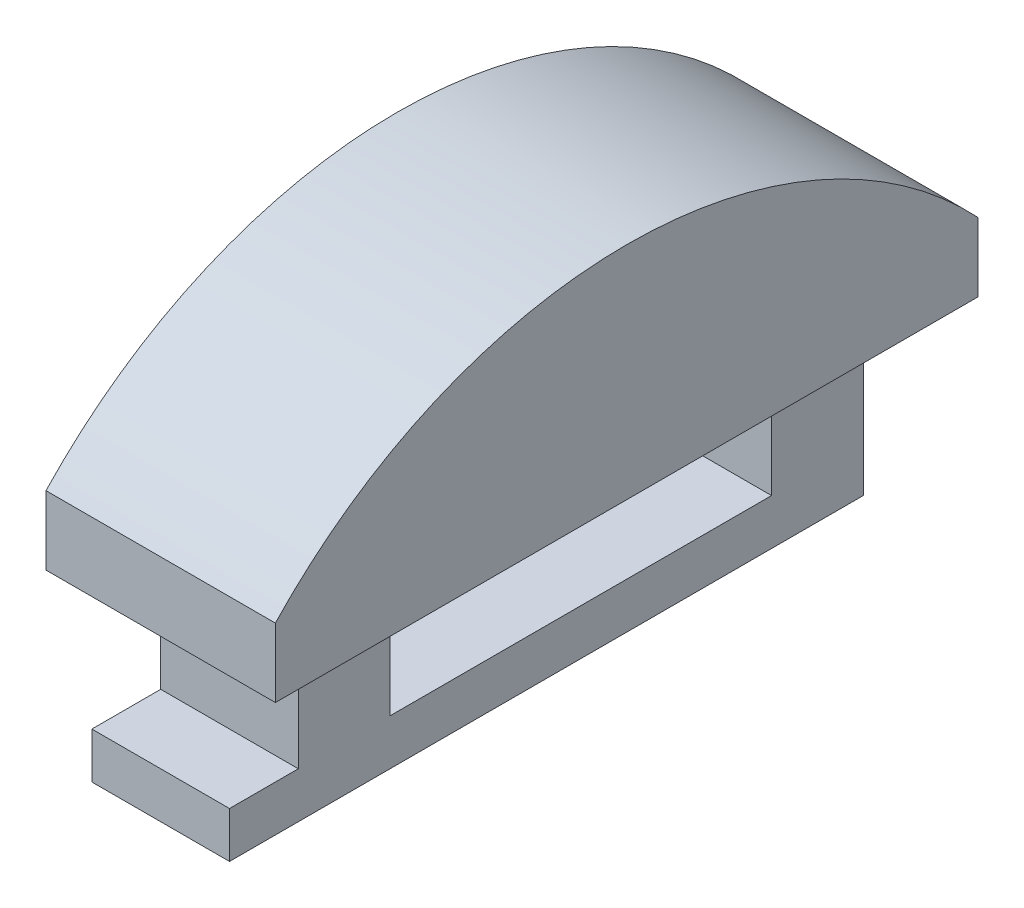
SolidWorks part; units mm, degrees
ref_plane "Спереди" through (0, 0, 0) normal (0, 0, 1) x (1, 0, 0)
ref_plane "Сверху" through (0, 0, 0) normal (0, 1, 0) x (1, 0, 0)
ref_plane "Справа" through (0, 0, 0) normal (1, 0, 0) x (0, 0, -1)
sketch "Эскиз1" plane through (0, 0, 0) normal (0, 1, 0) x (1, 0, 0)
  line L1 (-92.5718, 13.7126) -> (-82.5718, 13.7126)
  line L2 (-92.5718, 13.7126) -> (-92.5718, -16.9174)
  line L3 (-92.5718, -16.9174) -> (-82.5718, -16.9174)
  line L4 (-82.5718, 13.7126) -> (-82.5718, -16.9174)
extrude "Бобышка-Вытянуть1" add sketch "Эскиз1" along normal blind 3
sketch "Эскиз2" plane through (-82.5718, 0, 0) normal (1, 0, 0) x (0, 0, -1)
  line L0 (-16.9174, 3) -> (13.7126, 3)
  arc A0 (-16.9174, 3) -> (13.7126, 3) centre (-1.6024, -11.3684) cw
  dimension "D1" = 30.63
extrude "Бобышка-Вытянуть2" add sketch "Эскиз2" against normal blind 10
sketch "Эскиз3" plane through (0, 0, 0) normal (0, -1, 0) x (1, 0, 0)
  line L1 (-92.5718, -13.7126) -> (-92.5718, 16.9174) construction
  line L2 (-82.5718, 16.9174) -> (-82.5718, -13.7126) construction
  line L4 (-92.5718, 16.9174) -> (-82.5718, 16.9174) construction
  line L5 (-82.5718, -13.7126) -> (-92.5718, -13.7126) construction
  line L6 (-90.5718, 16.9174) -> (-90.5718, -13.7126) construction
  line L7 (-84.5718, 16.9174) -> (-84.5718, -13.7126) construction
  line L8 (-90.5718, -6.7126) -> (-84.5718, -6.7126)
  line L10 (-90.563, 9.9174) -> (-90.5718, 13.9174)
  line L11 (-90.5718, -10.7126) -> (-84.5718, -10.7126)
  line L12 (-84.5718, 9.9174) -> (-90.563, 9.9174)
  line L13 (-90.5718, 13.9174) -> (-84.5718, 13.9174)
  line L14 (-84.5718, 13.9174) -> (-84.5718, 9.9174)
  line L15 (-90.5718, -6.7126) -> (-90.5718, -10.7126)
  line L16 (-84.5718, -6.7126) -> (-84.5718, -10.7126)
  dimension "D1" = 3
  dimension "D2" = 3
  dimension "D3" = 2
  dimension "D4" = 2
  dimension "D6" = 4
  dimension "D7" = 6
  dimension "D8" = 4
  dimension "D9" = 6
extrude "Бобышка-Вытянуть3" add sketch "Эскиз3" along normal blind 5
sketch "Эскиз4" plane through (0, -5, 0) normal (0, -1, 0) x (1, 0, 0)
  line L0 (-92.5718, 16.9174) -> (-82.5718, 16.9174) construction
  line L1 (-84.5718, -10.7126) -> (-90.5718, -10.7126)
  line L2 (-84.5718, -10.7126) -> (-84.5718, 16.9174)
  line L3 (-84.5718, 16.9174) -> (-90.5718, 16.9174)
  line L4 (-90.5718, -10.7126) -> (-90.5718, 16.9174)
  line L5 (-84.5718, 13.9174) -> (-90.5718, 13.9174) construction
  circle A0 centre (-87.5718, 11.9174) radius 1.5
  circle A1 centre (-87.5718, -8.7126) radius 1.5
  dimension "D2" = 2
  dimension "D3" = 3
  dimension "D1" = 3
  dimension "D4" = 2
extrude "Бобышка-Вытянуть4" add sketch "Эскиз4" along normal blind 2
